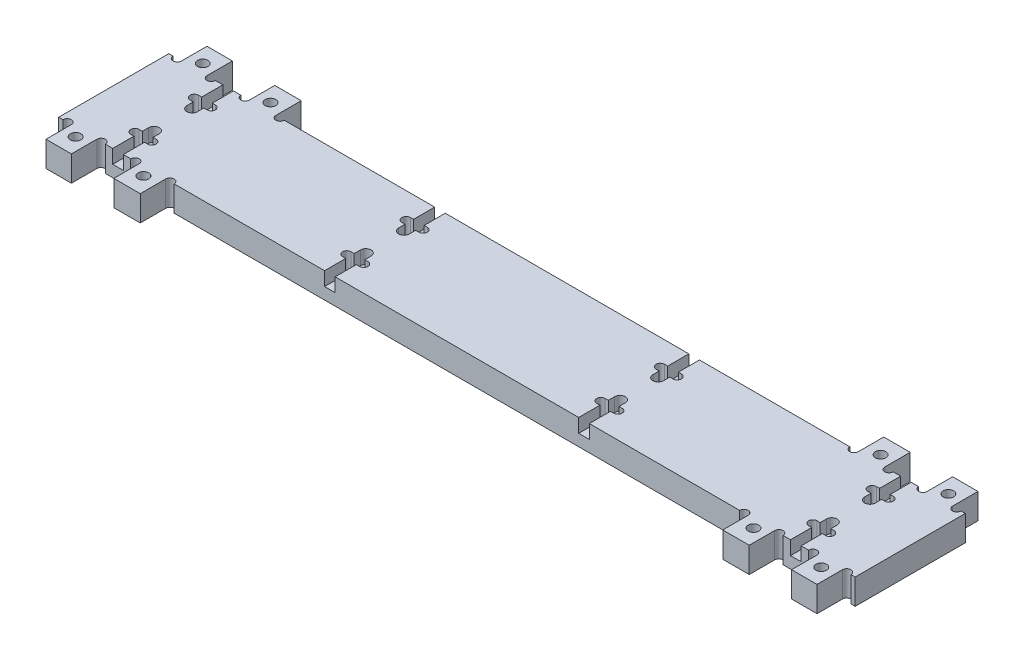
SolidWorks part; units mm, degrees
material "HDPE-green"
ref_plane "Front Plane" through (0, 0, 0) normal (0, 0, 1) x (1, 0, 0)
ref_plane "Top Plane" through (0, 0, 0) normal (0, 1, 0) x (1, 0, 0)
ref_plane "Right Plane" through (0, 0, 0) normal (1, 0, 0) x (0, 0, -1)
sketch "Sketch1" plane through (0, 0, 0) normal (0, 1, 0) x (1, 0, 0)
  line L1 (188, -26) -> (-188, -26)
  line L2 (188, -26) -> (188, 26)
  line L3 (188, 26) -> (-188, 26)
  line L4 (-188, -26) -> (-188, 26)
  line L5 (188, -26) -> (-188, 26) construction
  line L6 (188, 26) -> (-188, -26) construction
  point P0 (0, 0)
  dimension "D1" = 376
  dimension "D2" = 52
extrude "Boss-Extrude1" add sketch "Sketch1" along normal blind 12
sketch "Sketch6" plane through (0, 12, 0) normal (0, 1, 0) x (1, 0, 0)
  line L0 (-188, -26) -> (188, -26) construction
  line L1 (137.5, -26) -> (150, -26)
  line L2 (137.5, -26) -> (137.5, -38)
  line L3 (137.5, -38) -> (150, -38)
  line L4 (150, -26) -> (150, -38)
  line L5 (188, -26) -> (188, 26) construction
  line L6 (170, -26) -> (182, -26)
  line L7 (170, -26) -> (170, -38)
  line L8 (170, -38) -> (182, -38)
  line L9 (182, -26) -> (182, -38)
  dimension "D1" = 12
  dimension "D2" = 12
  dimension "D3" = 6
  dimension "D4" = 12
  dimension "D5" = 12.5
  dimension "D6" = 32
extrude "Boss-Extrude2" add sketch "Sketch6" against normal blind 12
hole_wizard "Ø5.0 (5) Diameter Hole1" positions "Sketch13" profile "Sketch12" hole size "Ø5.0" standard "ISO"
sketch "Sketch13" plane through (0, 12, 0) normal (0, 1, 0) x (-1, 0, 0)
  line L0 (-188, -26) -> (188, -26) construction
  point P1 (-176, 30)
  point P8 (-144, 30)
  point P10 (0, -26)
  dimension "D1" = 30
  dimension "D2" = 30
  dimension "D3" = 144
  dimension "D4" = 32
sketch "Sketch12" plane through (176, 12, 30) normal (1, 0, 0) x (0, 0, 1)
  line L0 (0, 0) -> (0, 13.5022)
  line L1 (0, 13.5022) -> (2.5, 12)
  line L2 (2.5, 12) -> (2.5, 0)
  line L5 (2.5, 0) -> (0, 0)
  line L10 (0, 13.5022) -> (-2.5, 12) construction
  line L11 (0, -6.35) -> (0, 107.95) construction
  dimension "Hole Dia." = 5
  dimension "Hole Depth" = 12
  dimension "Drill Angle" = 118
mirror "Mirror3" about plane through (0, 0, 0) normal (0, 0, 1) of "Ø5.0 (5) Diameter Hole1", "Boss-Extrude2"
mirror "Mirror4" about plane through (0, 0, 0) normal (1, 0, 0) of "Mirror3", "Boss-Extrude2", "Ø5.0 (5) Diameter Hole1"
sketch "Sketch8" plane through (0, 12, 0) normal (0, 1, 0) x (1, 0, 0)
  line L0 (-164, -14) -> (-156, -14) construction
  line L1 (-164, -12) -> (-156, -12)
  line L2 (-164, -16) -> (-156, -16)
  line L3 (-170, -26) -> (-150, -26) construction
  line L4 (-137.5, -26) -> (137.5, -26) construction
  arc A0 (-164, -12) -> (-164, -16) centre (-164, -14) ccw
  arc A1 (-156, -16) -> (-156, -12) centre (-156, -14) ccw
  point P2 (-160, -14)
  point P10 (0, -26)
  dimension "D1" = 12
  dimension "D2" = 2
  dimension "D3" = 8
  dimension "D4" = 160
extrude "Cut-Extrude2" cut sketch "Sketch8" against normal blind 8
sketch "Sketch11" plane through (0, 12, 0) normal (0, 1, 0) x (1, 0, 0)
  line L0 (-160, -9) -> (-160, -34.81) construction
  line L1 (-157.5, -9) -> (-157.5, -34.81)
  line L2 (-162.5, -9) -> (-162.5, -34.81)
  line L3 (-170, -26) -> (-150, -26) construction
  line L6 (-164, -16) -> (-156, -16) construction
  arc A0 (-157.5, -9) -> (-162.5, -9) centre (-160, -9) ccw
  arc A1 (-162.5, -34.81) -> (-157.5, -34.81) centre (-160, -34.81) ccw
  point P2 (-160, -21.905)
  point P9 (-160, -16)
  dimension "D1" = 2.5
  dimension "D2" = 17
extrude "Cut-Extrude5" cut sketch "Sketch11" against normal blind 6.5
sketch "Sketch7" plane through (0, 12, 0) normal (0, 1, 0) x (1, 0, 0)
  line L0 (-137.5, -26) -> (137.5, -26) construction
  line L1 (150, -26) -> (170, -26) construction
  line L2 (133.5, -26) -> (137.5, -26)
  line L3 (150, -26) -> (154, -26)
  line L4 (150, -26) -> (170, -26) construction
  line L5 (182, -26) -> (188, -26) construction
  line L6 (166, -26) -> (170, -26)
  line L7 (182, -26) -> (186, -26)
  arc A0 (137.5, -26) -> (133.5, -26) centre (135.5, -26) ccw
  arc A1 (150, -26) -> (154, -26) centre (152, -26) cw
  arc A2 (170, -26) -> (166, -26) centre (168, -26) ccw
  arc A3 (182, -26) -> (186, -26) centre (184, -26) cw
  dimension "D1" = 2
  dimension "D2" = 2
  dimension "D3" = 2
  dimension "D4" = 2
extrude "Cut-Extrude1" cut sketch "Sketch7" against normal up to next
pattern_linear "LPattern1" count 2 spacing 100 along (1, 0, 0) of "Cut-Extrude2", "Cut-Extrude5"
mirror "Mirror1" about plane through (0, 0, 0) normal (1, 0, 0) of "Cut-Extrude1", "LPattern1", "Cut-Extrude2", "Cut-Extrude5"
mirror "Mirror2" about plane through (0, 0, 0) normal (0, 0, 1) of "Mirror1", "LPattern1", "Cut-Extrude2", "Cut-Extrude5", "Cut-Extrude1"
